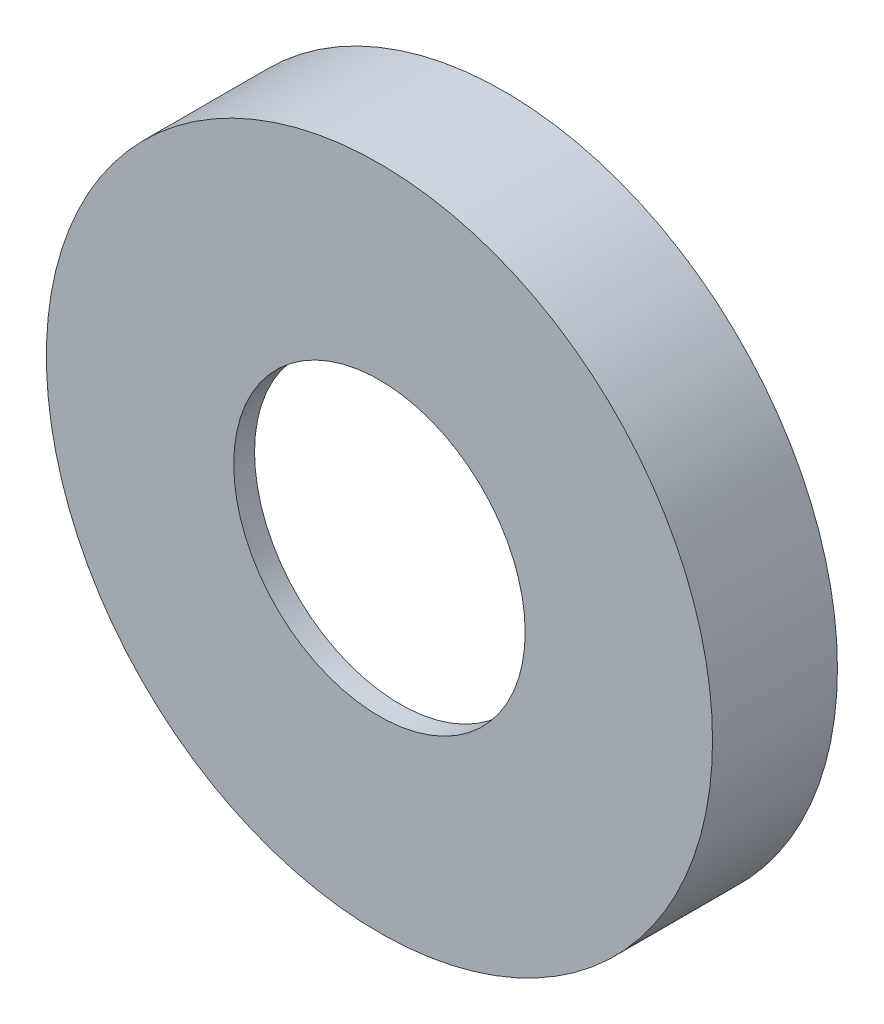
SolidWorks part; units mm, degrees
ref_plane "前视基准面" through (0, 0, 0) normal (0, 0, 1) x (1, 0, 0)
ref_plane "上视基准面" through (0, 0, 0) normal (0, 1, 0) x (1, 0, 0)
ref_plane "右视基准面" through (0, 0, 0) normal (1, 0, 0) x (0, 0, -1)
sketch "草图1" plane through (0, 0, 0) normal (0, 0, 1) x (1, 0, 0)
  circle A0 centre (0, 0) radius 8
  dimension "D1" = 16
extrude "拉伸1" add sketch "草图1" along normal blind 3
shell "抽壳2" thickness 0.5
sketch "草图2" plane through (0, 0, 3) normal (0, 0, 1) x (1, 0, 0)
  circle A0 centre (0, 0) radius 3.5
  dimension "D1" = 7
extrude "拉伸2" cut sketch "草图2" against normal through all
